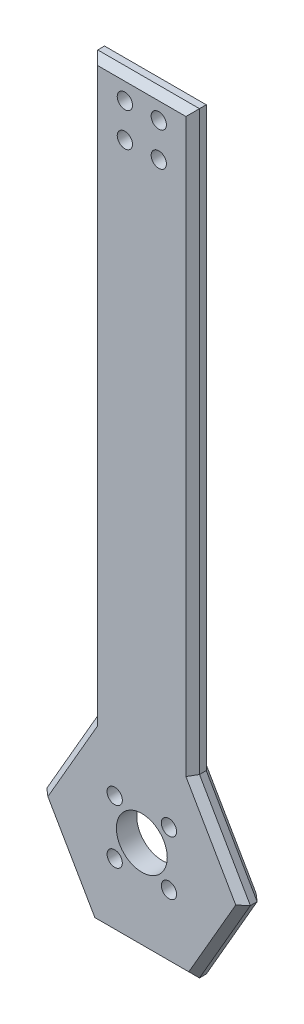
SolidWorks part; units mm, degrees
ref_plane "Front Plane" through (0, 0, 0) normal (1, 0, 0) x (0, 1, 0)
ref_plane "Top Plane" through (0, 0, 0) normal (0, 0, 1) x (0, 1, 0)
ref_plane "Right Plane" through (0, 0, 0) normal (0, 1, 0) x (-1, 0, 0)
sketch "Sketch2" plane through (0, 0, 0) normal (0, 0, 1) x (0, 1, 0)
  line L1 (-85, -15) -> (85, -15)
  line L2 (-85, -15) -> (-85, 15)
  line L3 (-85, 15) -> (85, 15)
  line L4 (85, -15) -> (85, 15)
  line L5 (-85, -15) -> (85, 15) construction
  line L6 (-85, 15) -> (85, -15) construction
  point P0 (0, 0)
  dimension "D1" = 170
  dimension "D2" = 30
extrude "Boss-Extrude2" add sketch "Sketch2" along normal blind 6
sketch "Sketch8" plane through (0, 0, 6) normal (0, 0, 1) x (1, 0, 0)
  line L1 (-30, -110.9808) -> (-15, -136.9615)
  line L2 (-15, -136.9615) -> (15, -136.9615)
  line L3 (15, -136.9615) -> (30, -110.9808)
  line L4 (30, -110.9808) -> (15, -85)
  line L5 (15, -85) -> (-15, -85)
  line L6 (-15, -85) -> (-30, -110.9808)
  circle A0 centre (0, -110.9808) radius 25.9808 construction
  dimension "D1" = 30
extrude "Boss-Extrude4" add sketch "Sketch8" against normal blind 6
chamfer "Chamfer1" distance 2 angle 45 16 edges at (-15, 0, 0) (-15, 0, 6) (-22.5, -97.9904, 0) (-22.5, -123.9711, 0) (0, -136.9615, 0) (22.5, -123.9711, 0) (22.5, -97.9904, 0) (15, 0, 0) (15, 0, 6) (0, 85, 0) (0, 85, 6) (22.5, -97.9904, 6) (22.5, -123.9711, 6) (0, -136.9615, 6) (-22.5, -123.9711, 6) (-22.5, -97.9904, 6)
hole_wizard "Hole6" positions "Sketch37" profile "Sketch38" legacy end condition through all
sketch "Sketch37" plane through (0, 0, 0) normal (0, 0, -1) x (-1, 0, 0)
  line L1 (13, -85.5359) -> (13, 83) construction
  line L2 (-13, 83) -> (-13, -85.5359) construction
  line L4 (-13.8453, -134.9615) -> (13.8453, -134.9615) construction
  point P0 (8, -116.9615)
  point P2 (-8, -116.9615)
  point P4 (-8, -100.9615)
  point P6 (8, -100.9615)
  dimension "D1" = 16
  dimension "D2" = 5
  dimension "D3" = 5
  dimension "D4" = 16
  dimension "D5" = 18
  dimension "D6" = 18
sketch "Sketch38" plane through (-8, -116.9615, 0) normal (1, 0, 0) x (0, 1, 0)
  line L0 (0, 0) -> (0, 6)
  line L1 (0, 6) -> (2.25, 6)
  line L2 (2.25, 6) -> (2.25, 0)
  line L3 (2.25, 0) -> (0, 0)
  line L4 (0, 110) -> (0, -10) construction
  dimension "Diameter" = 4.5
  dimension "Depth" = 6
hole_wizard "Hole4" positions "Sketch39" profile "Sketch40" legacy end condition through all
sketch "Sketch39" plane through (0, 0, 6) normal (0, 0, 1) x (1, 0, 0)
  line L0 (13, -85.5359) -> (13, 83) construction
  line L1 (-13, 83) -> (-13, -85.5359) construction
  line L2 (13, 83) -> (-13, 83) construction
  point P0 (-5, 68)
  point P2 (5, 68)
  point P4 (5, 78)
  point P6 (-5, 78)
  dimension "D1" = 8
  dimension "D2" = 8
  dimension "D3" = 5
  dimension "D4" = 10
sketch "Sketch40" plane through (-5, 68, 6) normal (1, 0, 0) x (0, -1, 0)
  line L0 (0, 0) -> (0, 6)
  line L1 (0, 6) -> (2.25, 6)
  line L2 (2.25, 6) -> (2.25, 0)
  line L3 (2.25, 0) -> (0, 0)
  line L4 (0, 110) -> (0, -10) construction
  dimension "Diameter" = 4.5
  dimension "Depth" = 6
hole_wizard "Hole7" positions "3DSketch2" profile "Sketch42" legacy end condition through all
sketch3d "3DSketch2"
  line L0 (-8, -116.9615, 6) -> (27.791, -81.1706, 6) construction
  line L1 (-8, -116.9615, 6) -> (-8, -116.9615, 0) construction
  line L3 (8, -116.9615, 6) -> (-31.6882, -77.2733, 6) construction
  line L4 (8, -116.9615, 6) -> (8, -116.9615, 0) construction
  point P0 (0, -108.9615, 6)
  point P13 (0, -108.9615, 6)
  point P16 (0, -108.9615, 6)
sketch "Sketch42" plane through (0, -108.9615, 6) normal (1, 0, 0) x (0, -1, 0)
  line L0 (0, 0) -> (0, 6)
  line L1 (0, 6) -> (7.5, 6)
  line L2 (7.5, 6) -> (7.5, 0)
  line L3 (7.5, 0) -> (0, 0)
  line L4 (0, 110) -> (0, -10) construction
  dimension "Diameter" = 15
  dimension "Depth" = 6
